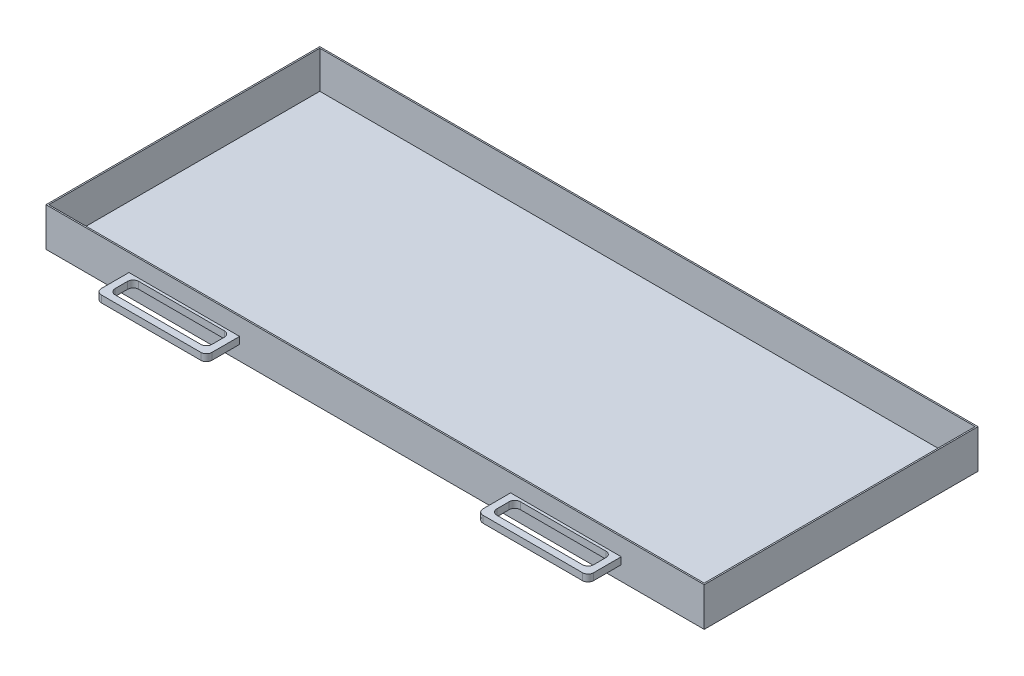
SolidWorks part; units mm, degrees
material "6061 Alloy"
ref_plane "Front Plane" through (0, 0, 0) normal (0, 0, 1) x (1, 0, 0)
ref_plane "Top Plane" through (0, 0, 0) normal (0, 1, 0) x (1, 0, 0)
ref_plane "Right Plane" through (0, 0, 0) normal (1, 0, 0) x (0, 0, -1)
sketch "Sketch1" plane through (0, 0, 0) normal (0, 1, 0) x (1, 0, 0)
  line L1 (-302.26, -125.73) -> (302.26, -125.73)
  line L2 (-302.26, -125.73) -> (-302.26, 125.73)
  line L3 (-302.26, 125.73) -> (302.26, 125.73)
  line L4 (302.26, -125.73) -> (302.26, 125.73)
  line L5 (-302.26, -125.73) -> (302.26, 125.73) construction
  line L6 (-302.26, 125.73) -> (302.26, -125.73) construction
  point P0 (0, 0)
  dimension "D1" = 604.52
  dimension "D2" = 251.46
extrude "Boss-Extrude1" add sketch "Sketch1" against normal blind 35.56
sketch "Sketch2" plane through (0, 0, 0) normal (0, 1, 0) x (1, 0, 0)
  line L1 (-300.99, -124.46) -> (300.99, -124.46)
  line L2 (-300.99, -124.46) -> (-300.99, 124.46)
  line L3 (-300.99, 124.46) -> (300.99, 124.46)
  line L4 (300.99, -124.46) -> (300.99, 124.46)
  line L5 (-300.99, -124.46) -> (300.99, 124.46) construction
  line L6 (-300.99, 124.46) -> (300.99, -124.46) construction
  point P0 (0, 0)
  dimension "D1" = 248.92
  dimension "D2" = 601.98
extrude "Cut-Extrude1" cut sketch "Sketch2" against normal blind 34.29
sketch "Sketch3" plane through (0, 0, 125.73) normal (0, 0, 1) x (1, 0, 0)
  line L0 (-302.26, -35.56) -> (-302.26, 0) construction
  line L1 (-226.06, -15.875) -> (-124.46, -15.875)
  line L2 (-226.06, -15.875) -> (-226.06, -22.225)
  line L3 (-226.06, -22.225) -> (-124.46, -22.225)
  line L4 (-124.46, -15.875) -> (-124.46, -22.225)
  line L9 (-302.26, 0) -> (302.26, 0) construction
  line L10 (0, -153.456) -> (0, 153.456) construction
  line L11 (226.06, -22.225) -> (124.46, -22.225)
  line L12 (124.46, -15.875) -> (124.46, -22.225)
  line L13 (226.06, -15.875) -> (124.46, -15.875)
  line L14 (226.06, -15.875) -> (226.06, -22.225)
  dimension "D1" = 101.6
  dimension "D2" = 6.35
  dimension "D3" = 76.2
  dimension "D4" = 15.875
extrude "Boss-Extrude2" add sketch "Sketch3" along normal blind 30.48
sketch "Sketch4" plane through (0, -15.875, 0) normal (0, 1, 0) x (1, 0, 0)
  line L0 (-124.46, -125.73) -> (-226.06, -125.73) construction
  line L1 (-219.71, -128.27) -> (-130.81, -128.27)
  line L2 (-219.71, -128.27) -> (-219.71, -149.86)
  line L3 (-219.71, -149.86) -> (-130.81, -149.86)
  line L4 (-130.81, -128.27) -> (-130.81, -149.86)
  line L5 (-124.46, -156.21) -> (-226.06, -156.21) construction
  line L6 (-124.46, -156.21) -> (-124.46, -125.73) construction
  line L7 (-226.06, -156.21) -> (-226.06, -125.73) construction
  line L8 (0, -153.456) -> (0, 153.456) construction
  line L9 (219.71, -149.86) -> (130.81, -149.86)
  line L10 (130.81, -128.27) -> (130.81, -149.86)
  line L11 (219.71, -128.27) -> (130.81, -128.27)
  line L12 (219.71, -128.27) -> (219.71, -149.86)
  dimension "D1" = 2.54
  dimension "D2" = 6.35
  dimension "D3" = 6.35
  dimension "D4" = 6.35
extrude "Cut-Extrude2" cut sketch "Sketch4" against normal through all
fillet "Fillet1" radius 5.08 8 edges at (-219.71, -19.05, 149.86) (-219.71, -19.05, 128.27) (-130.81, -19.05, 128.27) (-130.81, -19.05, 149.86) (130.81, -19.05, 149.86) (219.71, -19.05, 149.86) (130.81, -19.05, 128.27) (219.71, -19.05, 128.27)
fillet "Fillet2" radius 5.08 4 edges at (124.46, -19.05, 156.21) (226.06, -19.05, 156.21) (-124.46, -19.05, 156.21) (-226.06, -19.05, 156.21)
